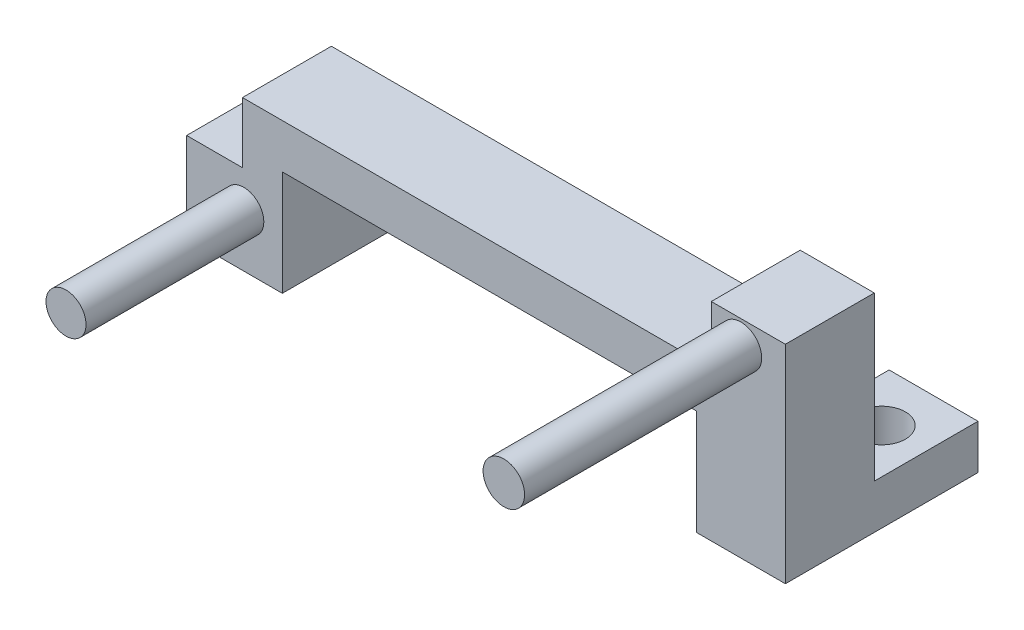
SolidWorks part; units mm, degrees
ref_plane "Front Plane" through (0, 0, 0) normal (0, 0, 1) x (1, 0, 0)
ref_plane "Top Plane" through (0, 0, 0) normal (0, 1, 0) x (1, 0, 0)
ref_plane "Right Plane" through (0, 0, 0) normal (1, 0, 0) x (0, 0, -1)
sketch "Sketch1" plane through (0, 0, 0) normal (0, 0, 1) x (1, 0, 0)
  line L1 (-3.4341, 3.4024) -> (0.5659, 3.4024)
  line L2 (-3.4341, 3.4024) -> (-3.4341, -10.5976)
  line L3 (-3.4341, -10.5976) -> (0.5659, -10.5976)
  line L4 (0.5659, 3.4024) -> (0.5659, -10.5976)
  dimension "D1" = 14
  dimension "D2" = 4
extrude "Boss-Extrude1" add sketch "Sketch1" along normal blind 3
sketch "Sketch2" plane through (0, 0, 0) normal (0, 0, -1) x (-1, 0, 0)
  line L0 (1.4341, -10.5976) -> (1.4341, 1.8024) construction
  line L1 (3.4341, -10.5976) -> (-0.5659, -10.5976) construction
  circle A0 centre (1.4341, 1.8024) radius 1.4
  dimension "D2" = 2.8
  dimension "D1" = 12.4
extrude "Boss-Extrude2" add sketch "Sketch2" along normal blind 16
sketch "Sketch3" plane through (0, 0, 3) normal (0, 0, 1) x (1, 0, 0)
  line L0 (-3.4341, 3.4024) -> (-3.4341, -10.5976) construction
  line L1 (-3.4341, -9.5976) -> (0.5659, -9.5976)
  line L2 (-3.4341, -9.5976) -> (-3.4341, -10.5976)
  line L3 (-3.4341, -10.5976) -> (0.5659, -10.5976)
  line L4 (0.5659, -9.5976) -> (0.5659, -10.5976)
  dimension "D1" = 1
extrude "Boss-Extrude4" add sketch "Sketch3" along normal blind 6
sketch "Sketch7" plane through (-3.4341, 0, 0) normal (-1, 0, 0) x (0, 0, 1)
  line L0 (0, 3.4024) -> (0, -10.5976) construction
  line L1 (0, -1.4976) -> (3, -1.4976)
  line L2 (0, -1.4976) -> (0, -3.4976)
  line L3 (0, -3.4976) -> (3, -3.4976)
  line L4 (3, -1.4976) -> (3, -3.4976)
  line L5 (3, 3.4024) -> (3, -9.5976) construction
  line L6 (9, -10.5976) -> (0, -10.5976) construction
  dimension "D1" = 7.1
  dimension "D2" = 2
extrude "Boss-Extrude5" add sketch "Sketch7" along normal blind 30.95
sketch "Sketch8" plane through (-34.3841, 0, 0) normal (-1, 0, 0) x (0, 0, 1)
  line L1 (0, -1.4976) -> (3, -1.4976)
  line L2 (0, -1.4976) -> (0, -3.4976)
  line L3 (0, -3.4976) -> (3, -3.4976)
  line L4 (3, -1.4976) -> (3, -3.4976)
extrude "Boss-Extrude6" add sketch "Sketch8" along normal blind 1
sketch "Sketch9" plane through (0, 0, 0) normal (0, 0, -1) x (-1, 0, 0)
  line L0 (35.3841, -3.4976) -> (3.4341, -3.4976) construction
  line L1 (35.3841, -1.4976) -> (34.3841, -1.4976)
  line L2 (35.3841, -1.4976) -> (35.3841, -3.4976)
  line L3 (35.3841, -3.4976) -> (34.3841, -3.4976)
  line L4 (34.3841, -1.4976) -> (34.3841, -3.4976)
  dimension "D1" = 1
extrude "Boss-Extrude7" add sketch "Sketch9" along normal blind 3
sketch "Sketch10" plane through (0, 0, -3) normal (0, 0, -1) x (-1, 0, 0)
  line L0 (34.3841, -3.4976) -> (35.3841, -3.4976) construction
  line L1 (34.3841, -1.4976) -> (35.3841, -1.4976)
  line L2 (34.3841, -1.4976) -> (34.3841, -3.4976)
  line L3 (34.3841, -3.4976) -> (35.3841, -3.4976)
  line L4 (35.3841, -1.4976) -> (35.3841, -3.4976)
  line L5 (35.3841, -3.4976) -> (35.3841, -1.4976) construction
extrude "Boss-Extrude8" add sketch "Sketch10" along normal blind 5.92
sketch "Sketch11" plane through (0, 0, -8.92) normal (0, 0, -1) x (-1, 0, 0)
  line L1 (34.3841, -1.4976) -> (35.3841, -1.4976)
  line L2 (34.3841, -1.4976) -> (34.3841, -3.4976)
  line L3 (34.3841, -3.4976) -> (35.3841, -3.4976)
  line L4 (35.3841, -1.4976) -> (35.3841, -3.4976)
extrude "Boss-Extrude9" add sketch "Sketch11" along normal blind 4
sketch "Sketch12" plane through (0, -3.4976, 0) normal (0, -1, 0) x (1, 0, 0)
  line L0 (-35.3841, 3) -> (-35.3841, -7.78) construction
  line L1 (-35.3841, -12.92) -> (-35.3841, 3) construction
  line L2 (-34.3841, -12.92) -> (-34.3841, 0) construction
  line L3 (-35.3841, -7.78) -> (-34.3841, -7.78)
  line L4 (-35.3841, -7.78) -> (-35.3841, -10.78)
  line L5 (-35.3841, -10.78) -> (-34.3841, -10.78)
  line L6 (-34.3841, -7.78) -> (-34.3841, -10.78)
  dimension "D1" = 10.78
  dimension "D2" = 3
extrude "Boss-Extrude14" add sketch "Sketch12" along normal blind 0.93
sketch "Sketch13" plane through (0, -3.4976, 0) normal (0, -1, 0) x (1, 0, 0)
  line L0 (-34.3841, 0) -> (-3.4341, 0) construction
  line L1 (-35.3841, 3) -> (-32.3841, 3)
  line L2 (-35.3841, 3) -> (-35.3841, 0)
  line L3 (-35.3841, 0) -> (-32.3841, 0)
  line L4 (-32.3841, 3) -> (-32.3841, 0)
  dimension "D1" = 3
extrude "Boss-Extrude15" add sketch "Sketch13" along normal blind 7.1
sketch "Sketch14" plane through (0, 0, 3) normal (0, 0, 1) x (1, 0, 0)
  line L0 (-32.3841, -10.5976) -> (-35.3841, -10.5976) construction
  line L1 (-33.6531, -10.5976) -> (-36.9872, -10.5976)
  line L2 (-33.6531, -10.5976) -> (-33.6531, 3.2634)
  line L3 (-33.6531, 3.2634) -> (-36.9872, 3.2634)
  line L4 (-36.9872, -10.5976) -> (-36.9872, 3.2634)
extrude "Cut-Extrude3" cut sketch "Sketch14" against normal blind 10
sketch "Sketch15" plane through (-35.3841, 0, 0) normal (-1, 0, 0) x (0, 0, 1)
  line L1 (-12.92, -1.4976) -> (-6.7133, -1.4976)
  line L2 (-12.92, -1.4976) -> (-12.92, -5.1581)
  line L3 (-12.92, -5.1581) -> (-6.7133, -5.1581)
  line L4 (-6.7133, -1.4976) -> (-6.7133, -5.1581)
extrude "Cut-Extrude4" cut sketch "Sketch15" against normal blind 10
sketch "Sketch16" plane through (-33.6531, 0, 0) normal (-1, 0, 0) x (0, 0, 1)
  line L1 (0, -1.4976) -> (3, -1.4976)
  line L2 (0, -1.4976) -> (0, -10.5976)
  line L3 (0, -10.5976) -> (3, -10.5976)
  line L4 (3, -1.4976) -> (3, -10.5976)
extrude "Boss-Extrude16" add sketch "Sketch16" along normal blind 0.12
sketch "Sketch18" plane through (-33.7731, 0, 0) normal (-1, 0, 0) x (0, 0, 1)
  line L1 (0, -1.4976) -> (3, -1.4976)
  line L2 (0, -1.4976) -> (0, -10.5976)
  line L3 (0, -10.5976) -> (3, -10.5976)
  line L4 (3, -1.4976) -> (3, -10.5976)
extrude "Boss-Extrude18" add sketch "Sketch18" along normal blind 0.41
sketch "Sketch19" plane through (-34.1831, 0, 0) normal (-1, 0, 0) x (0, 0, 1)
  line L1 (0, -1.4976) -> (3, -1.4976)
  line L2 (0, -1.4976) -> (0, -10.5976)
  line L3 (0, -10.5976) -> (3, -10.5976)
  line L4 (3, -1.4976) -> (3, -10.5976)
extrude "Boss-Extrude19" add sketch "Sketch19" along normal blind 0.89
sketch "Sketch20" plane through (-35.0731, 0, 0) normal (-1, 0, 0) x (0, 0, 1)
  line L0 (0, -1.4976) -> (0, -10.5976) construction
  line L1 (0, -4.5976) -> (3, -4.5976)
  line L2 (0, -4.5976) -> (0, -10.5976)
  line L3 (0, -10.5976) -> (3, -10.5976)
  line L4 (3, -4.5976) -> (3, -10.5976)
  line L5 (9, -10.5976) -> (0, -10.5976) construction
  line L6 (3, -10.5976) -> (3, -1.4976) construction
  dimension "D1" = 3.1
extrude "Boss-Extrude20" add sketch "Sketch20" along normal blind 3.77
sketch "Sketch21" plane through (0, 0, 0) normal (0, 0, -1) x (-1, 0, 0)
  line L0 (35.0731, -4.5976) -> (35.0731, -5.5976) construction
  line L1 (35.0731, -5.5976) -> (34.9841, -5.5976) construction
  line L2 (34.9841, -5.5976) -> (34.9841, -7.0476) construction
  line L3 (32.3841, -10.5976) -> (32.3841, -3.4976) construction
  circle A0 centre (34.9841, -7.0476) radius 1.35
  dimension "D4" = 2.7
  dimension "D2" = 2.6
  dimension "D1" = 1
  dimension "D3" = 1.45
extrude "Boss-Extrude23" add sketch "Sketch21" along normal blind 12
sketch "Sketch23" plane through (0, 0, 3) normal (0, 0, 1) x (1, 0, 0)
  line L0 (-38.8431, -10.5976) -> (-38.8431, -4.5976)
  line L1 (-38.8431, -4.5976) -> (-35.0731, -4.5976)
  line L2 (-35.0731, -4.5976) -> (-35.0731, -1.4976)
  line L3 (-35.0731, -1.4976) -> (-3.4341, -1.4976)
  line L4 (-3.4341, -1.4976) -> (-3.4341, 3.4024)
  line L5 (-3.4341, 3.4024) -> (0.5659, 3.4024)
  line L6 (0.5659, 3.4024) -> (0.5659, -9.5976)
  line L7 (0.5659, -9.5976) -> (-3.4341, -9.5976)
  line L8 (-3.4341, -9.5976) -> (-3.4341, -3.4976)
  line L9 (-3.4341, -3.4976) -> (-32.3841, -3.4976)
  line L10 (-32.3841, -3.4976) -> (-32.3841, -10.5976)
  line L11 (-32.3841, -10.5976) -> (-38.8431, -10.5976)
extrude "Boss-Extrude24" add sketch "Sketch23" along normal blind 3
sketch "Sketch24" plane through (0, 0, 9) normal (0, 0, 1) x (1, 0, 0)
  line L1 (-3.4341, -9.5976) -> (0.5659, -9.5976)
  line L2 (-3.4341, -9.5976) -> (-3.4341, -10.5976)
  line L3 (-3.4341, -10.5976) -> (0.5659, -10.5976)
  line L4 (0.5659, -9.5976) -> (0.5659, -10.5976)
extrude "Boss-Extrude25" add sketch "Sketch24" along normal blind 4
sketch "Sketch25" plane through (0, -9.5976, 0) normal (0, 1, 0) x (1, 0, 0)
  line L1 (-3.4341, -6) -> (0.5659, -6)
  line L2 (-3.4341, -6) -> (-3.4341, -13)
  line L3 (-3.4341, -13) -> (0.5659, -13)
  line L4 (0.5659, -6) -> (0.5659, -13)
extrude "Boss-Extrude26" add sketch "Sketch25" along normal blind 2
sketch "Sketch26" plane through (0, 0, 6) normal (0, 0, 1) x (1, 0, 0)
  line L0 (-38.8431, -4.5976) -> (-38.8431, -10.5976) construction
  line L1 (-32.3841, -10.5976) -> (-38.8431, -10.5976)
  line L2 (-32.3841, -10.5976) -> (-32.3841, -7.5976)
  line L3 (-32.3841, -7.5976) -> (-38.8431, -7.5976)
  line L4 (-38.8431, -10.5976) -> (-38.8431, -7.5976)
  dimension "D1" = 3
extrude "Boss-Extrude27" add sketch "Sketch26" along normal blind 7
sketch "Sketch27" plane through (0, -7.5976, 0) normal (0, 1, 0) x (1, 0, 0)
  line L0 (-38.8431, -9.5) -> (-32.3841, -9.5) construction
  line L1 (-38.8431, -13) -> (-38.8431, -6) construction
  line L2 (-32.3841, -13) -> (-32.3841, -6) construction
  line L3 (-35.6136, -13) -> (-35.6136, -6) construction
  line L4 (-32.3841, -13) -> (-38.8431, -13) construction
  line L5 (-32.3841, -6) -> (-38.8431, -6) construction
  circle A0 centre (-35.6136, -9.5) radius 1.6
  dimension "D1" = 3.2
extrude "Cut-Extrude5" cut sketch "Sketch27" against normal blind 7
sketch "Sketch28" plane through (0, -7.5976, 0) normal (0, 1, 0) x (1, 0, 0)
  line L0 (-1.4341, -13) -> (-1.4341, -6) construction
  line L1 (-3.4341, -13) -> (0.5659, -13) construction
  line L2 (0.5659, -6) -> (-3.4341, -6) construction
  line L3 (-3.4341, -9.5) -> (0.5659, -9.5) construction
  line L4 (-3.4341, -6) -> (-3.4341, -13) construction
  line L5 (0.5659, -13) -> (0.5659, -6) construction
  circle A0 centre (-1.4341, -9.5) radius 1.6
  dimension "D1" = 3.2
extrude "Cut-Extrude6" cut sketch "Sketch28" against normal blind 7
sketch "Sketch30" plane through (0.5659, 0, 0) normal (1, 0, 0) x (0, 0, -1)
  line L1 (-6, -7.5976) -> (-13, -7.5976)
  line L2 (-6, -7.5976) -> (-6, -10.5976)
  line L3 (-6, -10.5976) -> (-13, -10.5976)
  line L4 (-13, -7.5976) -> (-13, -10.5976)
extrude "Boss-Extrude29" add sketch "Sketch30" along normal blind 1
sketch "Sketch31" plane through (-3.4341, 0, 0) normal (-1, 0, 0) x (0, 0, 1)
  line L1 (6, -7.5976) -> (13, -7.5976)
  line L2 (6, -7.5976) -> (6, -10.5976)
  line L3 (6, -10.5976) -> (13, -10.5976)
  line L4 (13, -7.5976) -> (13, -10.5976)
extrude "Boss-Extrude30" add sketch "Sketch31" along normal blind 1
sketch "Sketch32" plane through (-3.4341, 0, 0) normal (-1, 0, 0) x (0, 0, 1)
  line L1 (0, -3.4976) -> (6, -3.4976)
  line L2 (0, -3.4976) -> (0, -10.5976)
  line L3 (0, -10.5976) -> (6, -10.5976)
  line L4 (6, -3.4976) -> (6, -10.5976)
extrude "Boss-Extrude31" add sketch "Sketch32" along normal blind 1
sketch "Sketch33" plane through (0, -1.4976, 0) normal (0, 1, 0) x (1, 0, 0)
  line L0 (-3.4341, -6) -> (-3.4341, 0) construction
  line L1 (-35.0731, 0) -> (-3.4341, 0)
  line L2 (-35.0731, 0) -> (-35.0731, -6)
  line L3 (-35.0731, -6) -> (-3.4341, -6)
  line L4 (-3.4341, 0) -> (-3.4341, -6)
  line L5 (-3.4341, -6) -> (-35.0731, -6) construction
extrude "Boss-Extrude32" add sketch "Sketch33" along normal blind 1
sketch "Sketch34" plane through (0.5659, 0, 0) normal (1, 0, 0) x (0, 0, -1)
  line L1 (-6, -10.5976) -> (0, -10.5976)
  line L2 (-6, -10.5976) -> (-6, 3.4024)
  line L3 (-6, 3.4024) -> (0, 3.4024)
  line L4 (0, -10.5976) -> (0, 3.4024)
extrude "Boss-Extrude33" add sketch "Sketch34" along normal blind 1
ref_plane "Plane1" through (0, 0, -86.5172) normal (0, 0, 1) x (1, 0, 0)
mirror "Mirror1" about plane through (0, 0, -86.5172) normal (0, 0, 1) of bodies 139
delete or keep bodies "Body-Delete/Keep 1" type delete bodies bodies 139
